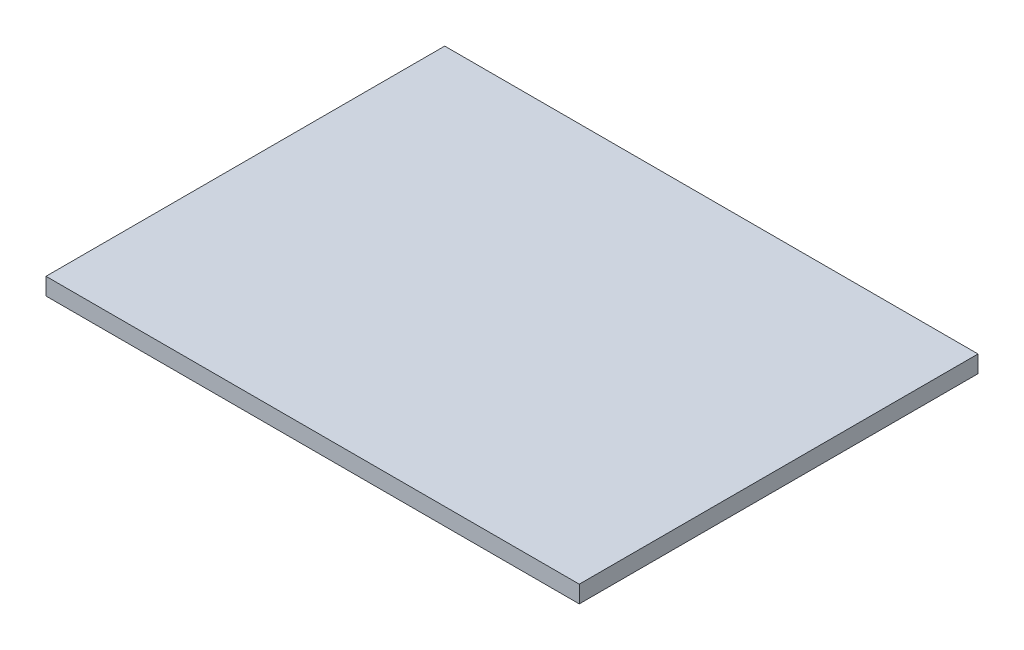
SolidWorks part; units mm, degrees
ref_plane "Front Plane" through (0, 0, 0) normal (0, 0, 1) x (1, 0, 0)
ref_plane "Top Plane" through (0, 0, 0) normal (0, 1, 0) x (1, 0, 0)
ref_plane "Right Plane" through (0, 0, 0) normal (1, 0, 0) x (0, 0, -1)
sketch "Sketch1" plane through (0, 0, 0) normal (0, 1, 0) x (1, 0, 0)
  line L1 (-109, 81.5) -> (109, 81.5)
  line L2 (-109, 81.5) -> (-109, -81.5)
  line L3 (-109, -81.5) -> (109, -81.5)
  line L4 (109, 81.5) -> (109, -81.5)
  line L5 (-109, 81.5) -> (109, -81.5) construction
  line L6 (-109, -81.5) -> (109, 81.5) construction
  point P0 (0, 0)
extrude "Boss-Extrude1" add sketch "Sketch1" along normal blind 7
